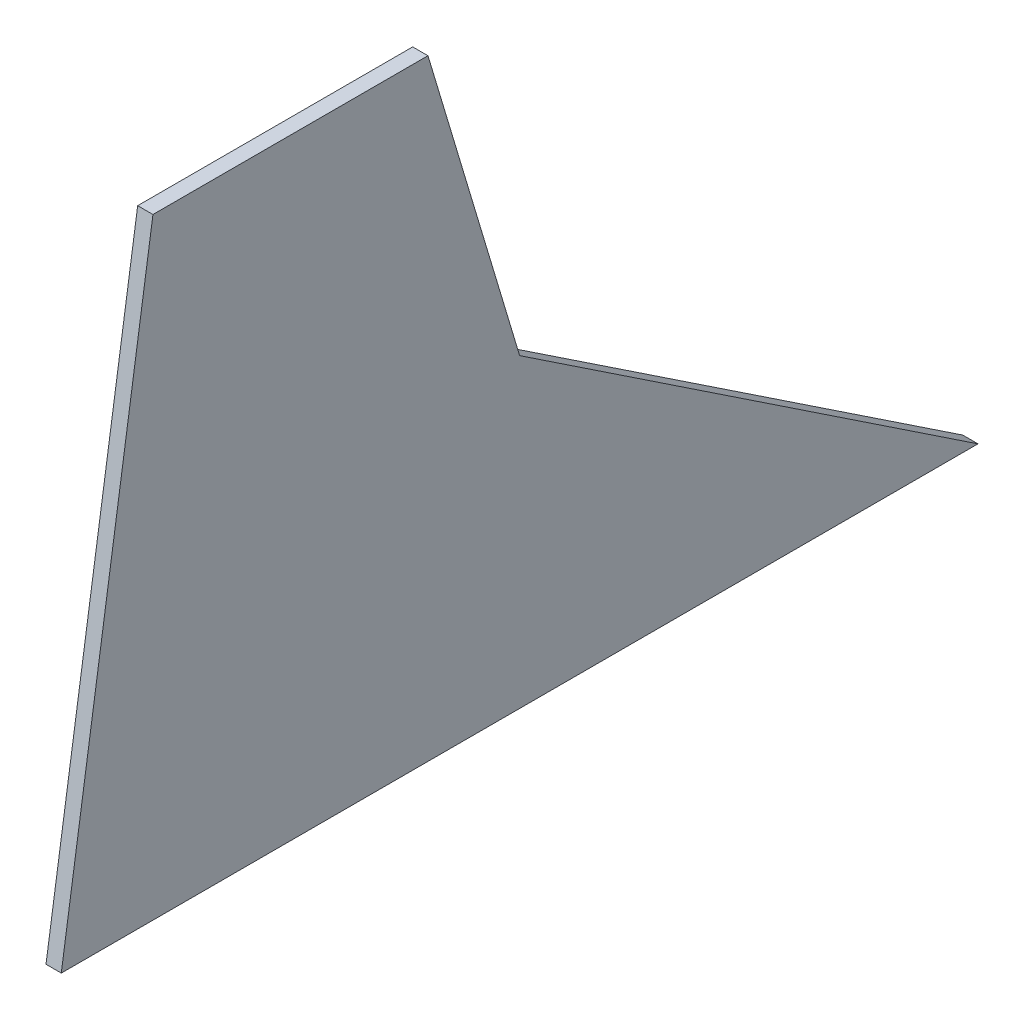
SolidWorks part; units mm, degrees
ref_plane "前视基准面" through (0, 0, 0) normal (0, 0, 1) x (1, 0, 0)
ref_plane "上视基准面" through (0, 0, 0) normal (0, 1, 0) x (1, 0, 0)
ref_plane "右视基准面" through (0, 0, 0) normal (1, 0, 0) x (0, 0, -1)
sketch "草图1" plane through (0, 0, 0) normal (1, 0, 0) x (0, 0, -1)
  line L0 (-60, 0) -> (120, 0)
  line L1 (120, 0) -> (60, 200)
  line L2 (60, 200) -> (-30, 200)
  line L3 (-30, 200) -> (-60, 0)
  line L4 (120, 0) -> (240, 0)
  line L5 (240, 0) -> (90, 100)
  line L6 (90, 100) -> (120, 0)
  line L7 (120, 0) -> (122.8855, -0.5611)
  dimension "D1" = 120
  dimension "D2" = 180
  dimension "D3" = 90
  dimension "D4" = 200
  dimension "D5" = 30
  dimension "D6" = 120
extrude "拉伸2" add sketch "草图1" along normal blind 5 contours L1 L2 L3 L0 | L4 L5 L6
